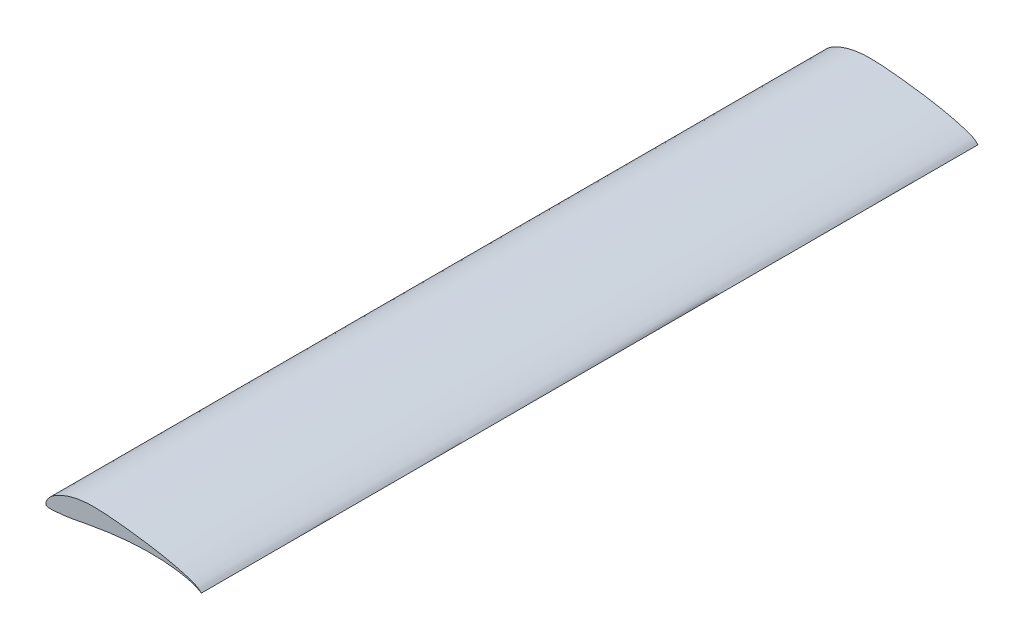
SolidWorks part; units mm, degrees
ref_plane "Front Plane" through (0, 0, 0) normal (0, 0, 1) x (1, 0, 0)
ref_plane "Top Plane" through (0, 0, 0) normal (0, 1, 0) x (1, 0, 0)
ref_plane "Right Plane" through (0, 0, 0) normal (1, 0, 0) x (0, 0, -1)
curve "Curve1"
  spline degree 3 poles (189.7628, 0.4947, 0) (190.6727, -0.123, 0) (189.8749, 0.4714, 0) (189.3453, 0.9911, 0) (188.1693, 2.0765, 0) (186.7819, 3.2312, 0) (184.8841, 4.3952, 0) (182.5241, 5.5233, 0) (179.675, 6.7006, 0) (176.3413, 7.9107, 0) (172.5383, 9.145, 0) (168.286, 10.3929, 0) (163.608, 11.6486, 0) (158.5302, 12.9003, 0) (153.0818, 14.1392, 0) (147.2951, 15.3574, 0) (141.2056, 16.5488, 0) (134.8488, 17.6986, 0) (128.2647, 18.8051, 0) (121.4914, 19.8543, 0) (114.5726, 20.848, 0) (107.5526, 21.7785, 0) (100.4822, 22.6427, 0) (93.4181, 23.4467, 0) (86.4187, 24.1704, 0) (79.541, 24.8, 0) (72.8334, 25.3003, 0) (66.3342, 25.6444, 0) (60.0796, 25.793, 0) (54.1015, 25.7772, 0) (48.4112, 25.4845, 0) (43.0065, 24.8913, 0) (37.8653, 24.0526, 0) (32.9864, 22.9661, 0) (28.3748, 21.6919, 0) (24.0501, 20.2528, 0) (20.0306, 18.6822, 0) (16.3413, 16.9888, 0) (12.994, 15.2068, 0) (10.0069, 13.3564, 0) (7.3989, 11.4629, 0) (5.1709, 9.5662, 0) (3.3552, 7.6458, 0) (1.9605, 5.7182, 0) (0.9303, 3.8429, 0) (0.2701, 2.0624, 0) (-0.0445, 0.419, 0) (0.0162, -0.9709, 0) (0.3741, -2.2457, 0) (1.7042, -2.8785, 0) (3.4926, -2.9673, 0) (5.9392, -3.0533, 0) (9.0159, -2.9207, 0) (12.688, -2.6769, 0) (16.9146, -2.2863, 0) (21.6525, -1.7579, 0) (26.8785, -1.0803, 0) (32.5902, -0.1332, 0) (38.8153, 1.0544, 0) (45.5849, 2.347, 0) (52.8659, 3.7117, 0) (60.6127, 5.092, 0) (68.7684, 6.436, 0) (77.2695, 7.6989, 0) (86.043, 8.8343, 0) (95.0099, 9.8092, 0) (104.0854, 10.5799, 0) (113.1786, 11.1261, 0) (122.1944, 11.4265, 0) (131.035, 11.4644, 0) (139.6018, 11.2374, 0) (147.7967, 10.7507, 0) (155.5211, 10.0106, 0) (162.6831, 9.0456, 0) (169.1894, 7.8836, 0) (174.9638, 6.5636, 0) (179.8998, 5.1511, 0) (183.9394, 3.6435, 0) (186.8216, 2.264, 0) (188.9465, 0.9883, 0) (189.7628, 0.4947, 0) (190.6727, -0.123, 0) (189.8749, 0.4714, 0) knots -0.009748 -0.004147 -0.001 0 0.00098 0.003649 0.007483 0.012095 0.017526 0.024052 0.031783 0.040678 0.05071 0.061833 0.073989 0.087118 0.101145 0.115991 0.13157 0.147788 0.164551 0.181758 0.199312 0.217095 0.23499 0.252857 0.270541 0.287887 0.304773 0.321101 0.336806 0.3518 0.366031 0.379616 0.392653 0.40517 0.417172 0.428604 0.439419 0.449597 0.459102 0.467908 0.475988 0.483309 0.489875 0.495803 0.501149 0.505903 0.510047 0.513579 0.516447 0.51935 0.523823 0.529974 0.537716 0.546968 0.557637 0.56962 0.582804 0.597247 0.613135 0.630444 0.649056 0.668822 0.689595 0.71119 0.733427 0.756094 0.778989 0.80189 0.824567 0.846792 0.868338 0.888978 0.908492 0.926659 0.943286 0.958169 0.971136 0.981956 0.990252 0.995853 0.999 1 1.00098 1.003649 1.007483 periodic
sketch "Sketch1" plane through (0, 0, 0) normal (0, 0, 1) x (1, 0, 0)
  spline S0 degree 3 poles (189.7628, 0.4947) (190.6727, -0.123) (189.8749, 0.4714) (189.3453, 0.9911) (188.1693, 2.0765) (186.7819, 3.2312) (184.8841, 4.3952) (182.5241, 5.5233) (179.675, 6.7006) (176.3413, 7.9107) (172.5383, 9.145) (168.286, 10.3929) (163.608, 11.6486) (158.5302, 12.9003) (153.0818, 14.1392) (147.2951, 15.3574) (141.2056, 16.5488) (134.8488, 17.6986) (128.2647, 18.8051) (121.4914, 19.8543) (114.5726, 20.848) (107.5526, 21.7785) (100.4822, 22.6427) (93.4181, 23.4467) (86.4187, 24.1704) (79.541, 24.8) (72.8334, 25.3003) (66.3342, 25.6444) (60.0796, 25.793) (54.1015, 25.7772) (48.4112, 25.4845) (43.0065, 24.8913) (37.8653, 24.0526) (32.9864, 22.9661) (28.3748, 21.6919) (24.0501, 20.2528) (20.0306, 18.6822) (16.3413, 16.9888) (12.994, 15.2068) (10.0069, 13.3564) (7.3989, 11.4629) (5.1709, 9.5662) (3.3552, 7.6458) (1.9605, 5.7182) (0.9303, 3.8429) (0.2701, 2.0624) (-0.0445, 0.419) (0.0162, -0.9709) (0.3741, -2.2457) (1.7042, -2.8785) (3.4926, -2.9673) (5.9392, -3.0533) (9.0159, -2.9207) (12.688, -2.6769) (16.9146, -2.2863) (21.6525, -1.7579) (26.8785, -1.0803) (32.5902, -0.1332) (38.8153, 1.0544) (45.5849, 2.347) (52.8659, 3.7117) (60.6127, 5.092) (68.7684, 6.436) (77.2695, 7.6989) (86.043, 8.8343) (95.0099, 9.8092) (104.0854, 10.5799) (113.1786, 11.1261) (122.1944, 11.4265) (131.035, 11.4644) (139.6018, 11.2374) (147.7967, 10.7507) (155.5211, 10.0106) (162.6831, 9.0456) (169.1894, 7.8836) (174.9638, 6.5636) (179.8998, 5.1511) (183.9394, 3.6435) (186.8216, 2.264) (188.9465, 0.9883) (189.7628, 0.4947) (190.6727, -0.123) (189.8749, 0.4714) knots -0.009748 -0.004147 -0.001 0 0.00098 0.003649 0.007483 0.012095 0.017526 0.024052 0.031783 0.040678 0.05071 0.061833 0.073989 0.087118 0.101145 0.115991 0.13157 0.147788 0.164551 0.181758 0.199312 0.217095 0.23499 0.252857 0.270541 0.287887 0.304773 0.321101 0.336806 0.3518 0.366031 0.379616 0.392653 0.40517 0.417172 0.428604 0.439419 0.449597 0.459102 0.467908 0.475988 0.483309 0.489875 0.495803 0.501149 0.505903 0.510047 0.513579 0.516447 0.51935 0.523823 0.529974 0.537716 0.546968 0.557637 0.56962 0.582804 0.597247 0.613135 0.630444 0.649056 0.668822 0.689595 0.71119 0.733427 0.756094 0.778989 0.80189 0.824567 0.846792 0.868338 0.888978 0.908492 0.926659 0.943286 0.958169 0.971136 0.981956 0.990252 0.995853 0.999 1 1.00098 1.003649 1.007483 only from (190.5, 0) to (190.5, 0) construction
  spline S1 degree 3 poles (189.7628, 0.4947) (190.6727, -0.123) (189.8749, 0.4714) (189.3453, 0.9911) (188.1693, 2.0765) (186.7819, 3.2312) (184.8841, 4.3952) (182.5241, 5.5233) (179.675, 6.7006) (176.3413, 7.9107) (172.5383, 9.145) (168.286, 10.3929) (163.608, 11.6486) (158.5302, 12.9003) (153.0818, 14.1392) (147.2951, 15.3574) (141.2056, 16.5488) (134.8488, 17.6986) (128.2647, 18.8051) (121.4914, 19.8543) (114.5726, 20.848) (107.5526, 21.7785) (100.4822, 22.6427) (93.4181, 23.4467) (86.4187, 24.1704) (79.541, 24.8) (72.8334, 25.3003) (66.3342, 25.6444) (60.0796, 25.793) (54.1015, 25.7772) (48.4112, 25.4845) (43.0065, 24.8913) (37.8653, 24.0526) (32.9864, 22.9661) (28.3748, 21.6919) (24.0501, 20.2528) (20.0306, 18.6822) (16.3413, 16.9888) (12.994, 15.2068) (10.0069, 13.3564) (7.3989, 11.4629) (5.1709, 9.5662) (3.3552, 7.6458) (1.9605, 5.7182) (0.9303, 3.8429) (0.2701, 2.0624) (-0.0445, 0.419) (0.0162, -0.9709) (0.3741, -2.2457) (1.7042, -2.8785) (3.4926, -2.9673) (5.9392, -3.0533) (9.0159, -2.9207) (12.688, -2.6769) (16.9146, -2.2863) (21.6525, -1.7579) (26.8785, -1.0803) (32.5902, -0.1332) (38.8153, 1.0544) (45.5849, 2.347) (52.8659, 3.7117) (60.6127, 5.092) (68.7684, 6.436) (77.2695, 7.6989) (86.043, 8.8343) (95.0099, 9.8092) (104.0854, 10.5799) (113.1786, 11.1261) (122.1944, 11.4265) (131.035, 11.4644) (139.6018, 11.2374) (147.7967, 10.7507) (155.5211, 10.0106) (162.6831, 9.0456) (169.1894, 7.8836) (174.9638, 6.5636) (179.8998, 5.1511) (183.9394, 3.6435) (186.8216, 2.264) (188.9465, 0.9883) (189.7628, 0.4947) (190.6727, -0.123) (189.8749, 0.4714) knots -0.009748 -0.004147 -0.001 0 0.00098 0.003649 0.007483 0.012095 0.017526 0.024052 0.031783 0.040678 0.05071 0.061833 0.073989 0.087118 0.101145 0.115991 0.13157 0.147788 0.164551 0.181758 0.199312 0.217095 0.23499 0.252857 0.270541 0.287887 0.304773 0.321101 0.336806 0.3518 0.366031 0.379616 0.392653 0.40517 0.417172 0.428604 0.439419 0.449597 0.459102 0.467908 0.475988 0.483309 0.489875 0.495803 0.501149 0.505903 0.510047 0.513579 0.516447 0.51935 0.523823 0.529974 0.537716 0.546968 0.557637 0.56962 0.582804 0.597247 0.613135 0.630444 0.649056 0.668822 0.689595 0.71119 0.733427 0.756094 0.778989 0.80189 0.824567 0.846792 0.868338 0.888978 0.908492 0.926659 0.943286 0.958169 0.971136 0.981956 0.990252 0.995853 0.999 1 1.00098 1.003649 1.007483 only from (190.5, 0) to (190.5, 0)
extrude "Boss-Extrude1" add sketch "Sketch1" along normal blind 952.5
sketch "Sketch2" plane through (0, 0, 0) normal (0, 0, -1) x (-1, 0, 0)
  line L0 (0, 0) -> (-190.5, 0) construction
  line L1 (-190.5, 0) -> (-190.5, -25.3291) construction
  line L2 (0, 0) -> (0, -25.3291) construction
  spline S0 degree 3 poles (-189.8749, 0.4714) (-190.6727, -0.123) (-189.7628, 0.4947) (-188.9465, 0.9883) (-186.8216, 2.264) (-183.9394, 3.6435) (-179.8998, 5.1511) (-174.9638, 6.5636) (-169.1894, 7.8836) (-162.6831, 9.0456) (-155.5211, 10.0106) (-147.7967, 10.7507) (-139.6018, 11.2374) (-131.035, 11.4644) (-122.1944, 11.4265) (-113.1786, 11.1261) (-104.0854, 10.5799) (-95.0099, 9.8092) (-86.043, 8.8343) (-77.2695, 7.6989) (-68.7684, 6.436) (-60.6127, 5.092) (-52.8659, 3.7117) (-45.5849, 2.347) (-38.8153, 1.0544) (-32.5902, -0.1332) (-26.8785, -1.0803) (-21.6525, -1.7579) (-16.9146, -2.2863) (-12.688, -2.6769) (-9.0159, -2.9207) (-5.9392, -3.0533) (-3.4926, -2.9673) (-1.7042, -2.8785) (-0.3741, -2.2457) (-0.0162, -0.9709) (0.0445, 0.419) (-0.2701, 2.0624) (-0.9303, 3.8429) (-1.9605, 5.7182) (-3.3552, 7.6458) (-5.1709, 9.5662) (-7.3989, 11.4629) (-10.0069, 13.3564) (-12.994, 15.2068) (-16.3413, 16.9888) (-20.0306, 18.6822) (-24.0501, 20.2528) (-28.3748, 21.6919) (-32.9864, 22.9661) (-37.8653, 24.0526) (-43.0065, 24.8913) (-48.4112, 25.4845) (-54.1015, 25.7772) (-60.0796, 25.793) (-66.3342, 25.6444) (-72.8334, 25.3003) (-79.541, 24.8) (-86.4187, 24.1704) (-93.4181, 23.4467) (-100.4822, 22.6427) (-107.5526, 21.7785) (-114.5726, 20.848) (-121.4914, 19.8543) (-128.2647, 18.8051) (-134.8488, 17.6986) (-141.2056, 16.5488) (-147.2951, 15.3574) (-153.0818, 14.1392) (-158.5302, 12.9003) (-163.608, 11.6486) (-168.286, 10.3929) (-172.5383, 9.145) (-176.3413, 7.9107) (-179.675, 6.7006) (-182.5241, 5.5233) (-184.8841, 4.3952) (-186.7819, 3.2312) (-188.1693, 2.0765) (-189.3453, 0.9911) (-189.8749, 0.4714) (-190.6727, -0.123) (-189.7628, 0.4947) knots -0.007483 -0.003649 -0.00098 0 0.001 0.004147 0.009748 0.018044 0.028864 0.041831 0.056714 0.073341 0.091508 0.111022 0.131662 0.153208 0.175433 0.19811 0.221011 0.243906 0.266573 0.28881 0.310405 0.331178 0.350944 0.369556 0.386865 0.402753 0.417196 0.43038 0.442363 0.453032 0.462284 0.470026 0.476177 0.48065 0.483553 0.486421 0.489953 0.494097 0.498851 0.504197 0.510125 0.516691 0.524012 0.532092 0.540898 0.550403 0.560581 0.571396 0.582828 0.59483 0.607347 0.620384 0.633969 0.6482 0.663194 0.678899 0.695227 0.712113 0.729459 0.747143 0.76501 0.782905 0.800688 0.818242 0.835449 0.852212 0.86843 0.884009 0.898855 0.912882 0.926011 0.938167 0.94929 0.959322 0.968217 0.975948 0.982474 0.987905 0.992517 0.996351 0.99902 1 1.001 1.004147 1.009748 only from (-190.5, 0) to (-190.5, 0) construction
  spline S1 degree 3 poles (-189.8749, 0.4714) (-190.6727, -0.123) (-189.7628, 0.4947) (-188.9465, 0.9883) (-186.8216, 2.264) (-183.9394, 3.6435) (-179.8998, 5.1511) (-174.9638, 6.5636) (-169.1894, 7.8836) (-162.6831, 9.0456) (-155.5211, 10.0106) (-147.7967, 10.7507) (-139.6018, 11.2374) (-131.035, 11.4644) (-122.1944, 11.4265) (-113.1786, 11.1261) (-104.0854, 10.5799) (-95.0099, 9.8092) (-86.043, 8.8343) (-77.2695, 7.6989) (-68.7684, 6.436) (-60.6127, 5.092) (-52.8659, 3.7117) (-45.5849, 2.347) (-38.8153, 1.0544) (-32.5902, -0.1332) (-26.8785, -1.0803) (-21.6525, -1.7579) (-16.9146, -2.2863) (-12.688, -2.6769) (-9.0159, -2.9207) (-5.9392, -3.0533) (-3.4926, -2.9673) (-1.7042, -2.8785) (-0.3741, -2.2457) (-0.0162, -0.9709) (0.0445, 0.419) (-0.2701, 2.0624) (-0.9303, 3.8429) (-1.9605, 5.7182) (-3.3552, 7.6458) (-5.1709, 9.5662) (-7.3989, 11.4629) (-10.0069, 13.3564) (-12.994, 15.2068) (-16.3413, 16.9888) (-20.0306, 18.6822) (-24.0501, 20.2528) (-28.3748, 21.6919) (-32.9864, 22.9661) (-37.8653, 24.0526) (-43.0065, 24.8913) (-48.4112, 25.4845) (-54.1015, 25.7772) (-60.0796, 25.793) (-66.3342, 25.6444) (-72.8334, 25.3003) (-79.541, 24.8) (-86.4187, 24.1704) (-93.4181, 23.4467) (-100.4822, 22.6427) (-107.5526, 21.7785) (-114.5726, 20.848) (-121.4914, 19.8543) (-128.2647, 18.8051) (-134.8488, 17.6986) (-141.2056, 16.5488) (-147.2951, 15.3574) (-153.0818, 14.1392) (-158.5302, 12.9003) (-163.608, 11.6486) (-168.286, 10.3929) (-172.5383, 9.145) (-176.3413, 7.9107) (-179.675, 6.7006) (-182.5241, 5.5233) (-184.8841, 4.3952) (-186.7819, 3.2312) (-188.1693, 2.0765) (-189.3453, 0.9911) (-189.8749, 0.4714) (-190.6727, -0.123) (-189.7628, 0.4947) knots -0.007483 -0.003649 -0.00098 0 0.001 0.004147 0.009748 0.018044 0.028864 0.041831 0.056714 0.073341 0.091508 0.111022 0.131662 0.153208 0.175433 0.19811 0.221011 0.243906 0.266573 0.28881 0.310405 0.331178 0.350944 0.369556 0.386865 0.402753 0.417196 0.43038 0.442363 0.453032 0.462284 0.470026 0.476177 0.48065 0.483553 0.486421 0.489953 0.494097 0.498851 0.504197 0.510125 0.516691 0.524012 0.532092 0.540898 0.550403 0.560581 0.571396 0.582828 0.59483 0.607347 0.620384 0.633969 0.6482 0.663194 0.678899 0.695227 0.712113 0.729459 0.747143 0.76501 0.782905 0.800688 0.818242 0.835449 0.852212 0.86843 0.884009 0.898855 0.912882 0.926011 0.938167 0.94929 0.959322 0.968217 0.975948 0.982474 0.987905 0.992517 0.996351 0.99902 1 1.001 1.004147 1.009748 only from (-190.5, 0) to (-190.5, 0) construction
sketch "Sketch3" plane through (0, 0, 952.5) normal (0, 0, 1) x (1, 0, 0)
  line L0 (0, 0) -> (0, -25.3291) construction
  line L1 (0, 0) -> (190.5, 0) construction
  line L2 (190.5, 0) -> (190.5, -25.3291) construction
  line L3 (0, 0) -> (0, -25.3291) construction
  line L4 (0, 0) -> (190.5, 0) construction
  line L5 (190.5, 0) -> (190.5, -25.3291) construction
sketch3d "3DSketch1"
  line L0 (0, 0, 952.5) -> (0, 0, 0) construction
ref_plane "Plane1" through (0, 0, 476.25) normal (0, 0, 1) x (1, 0, 0)
